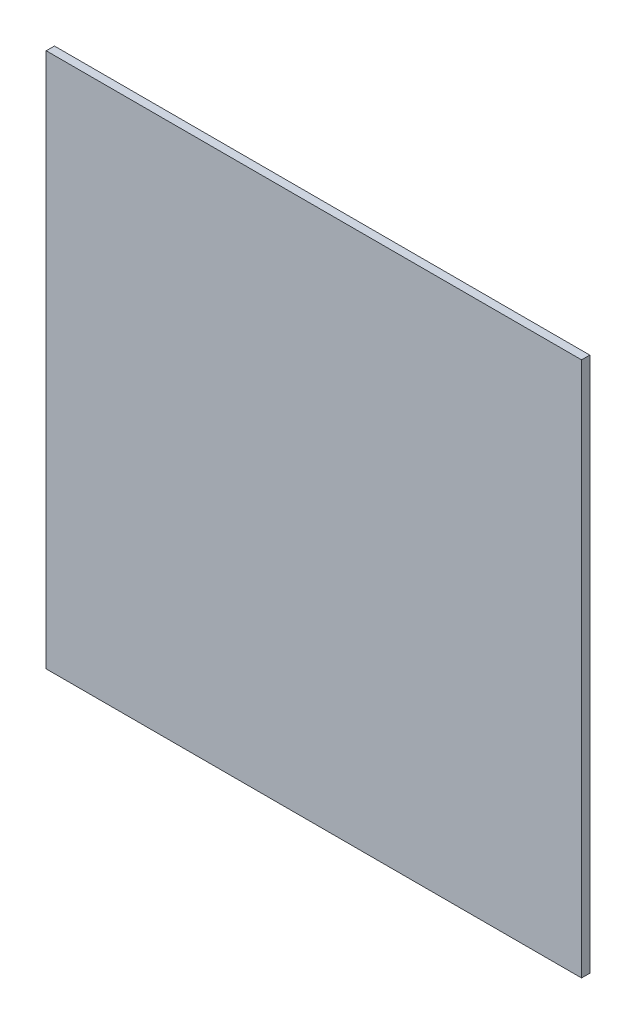
SolidWorks part; units mm, degrees
ref_plane "Plano frontal" through (0, 0, 0) normal (0, 0, 1) x (1, 0, 0)
ref_plane "Plano superior" through (0, 0, 0) normal (0, 1, 0) x (1, 0, 0)
ref_plane "Plano direito" through (0, 0, 0) normal (1, 0, 0) x (0, 0, -1)
sketch "Esboço1" plane through (0, 0, 0) normal (0, 0, 1) x (1, 0, 0)
  line L1 (-13.1175, 13.6559) -> (19.3825, 13.6559)
  line L2 (-13.1175, 13.6559) -> (-13.1175, -18.8441)
  line L3 (-13.1175, -18.8441) -> (19.3825, -18.8441)
  line L4 (19.3825, 13.6559) -> (19.3825, -18.8441)
  dimension "D1" = 32.5
  dimension "D2" = 32.5
extrude "Ressalto-extrusão1" add sketch "Esboço1" along normal blind 0.5
